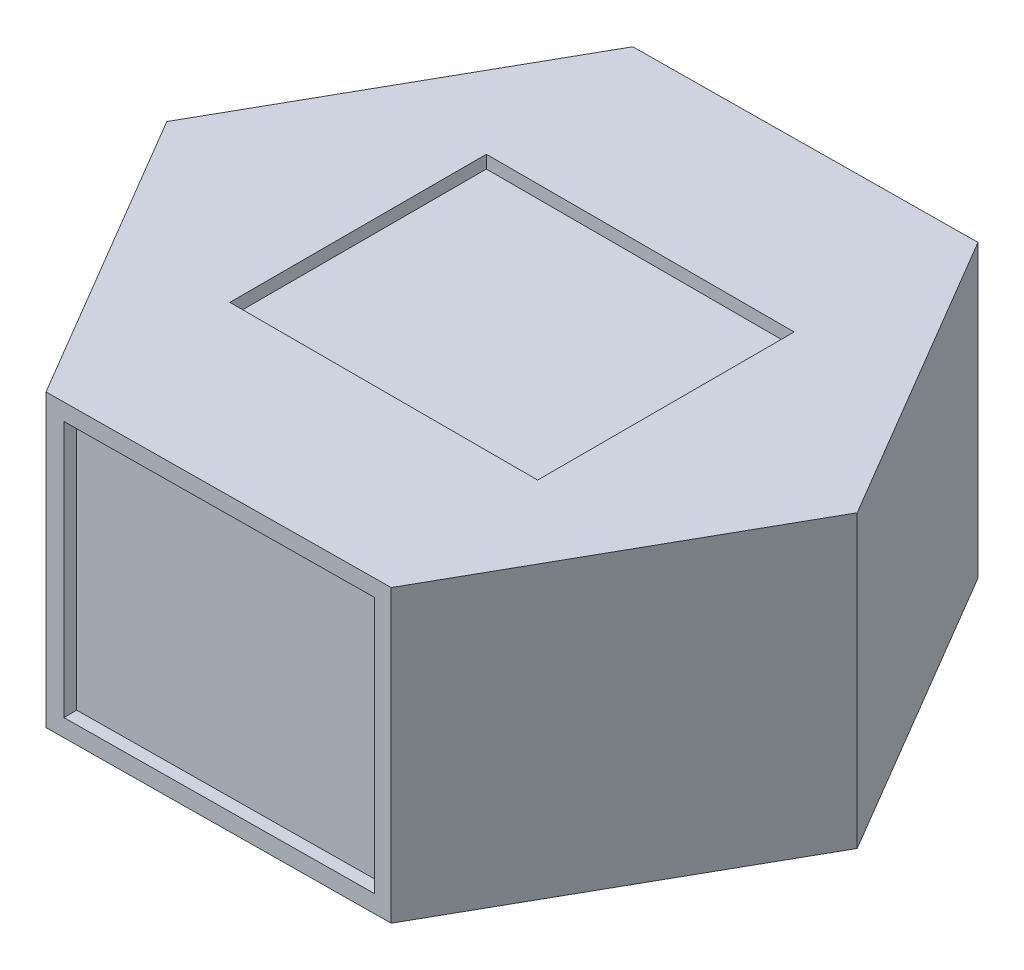
SolidWorks part; units mm, degrees
ref_plane "Front Plane" through (0, 0, 0) normal (0, 0, 1) x (1, 0, 0)
ref_plane "Top Plane" through (0, 0, 0) normal (0, 1, 0) x (1, 0, 0)
ref_plane "Right Plane" through (0, 0, 0) normal (1, 0, 0) x (0, 0, -1)
sketch "Sketch1" plane through (0, 0, 0) normal (0, 1, 0) x (1, 0, 0)
  line L1 (20.3231, -34.4525) -> (39.9983, 0.3741)
  line L2 (39.9983, 0.3741) -> (19.6752, 34.8265)
  line L3 (19.6752, 34.8265) -> (-20.3231, 34.4525)
  line L4 (-20.3231, 34.4525) -> (-39.9983, -0.3741)
  line L5 (-39.9983, -0.3741) -> (-19.6752, -34.8265)
  line L6 (-19.6752, -34.8265) -> (20.3231, -34.4525)
  circle A0 centre (0, 0) radius 34.641 construction
  dimension "D1" = 40
extrude "Boss-Extrude1" add sketch "Sketch1" along normal blind 34
sketch "Sketch2" plane through (0.324, 0, 34.6395) normal (0.0094, 0, 1) x (1, 0, -0.0094)
  line L1 (-17.9218, 32.043) -> (18.0782, 32.043)
  line L2 (-17.9218, 32.043) -> (-17.9218, 2.043)
  line L3 (-17.9218, 2.043) -> (18.0782, 2.043)
  line L4 (18.0782, 32.043) -> (18.0782, 2.043)
  dimension "D1" = 30
  dimension "D2" = 36
extrude "Cut-Extrude1" cut sketch "Sketch2" against normal blind 1.5
sketch "Sketch3" plane through (-0.324, 0, -34.6395) normal (-0.0094, 0, -1) x (-1, 0, 0.0094)
  line L1 (-18.0909, 32.0618) -> (17.9091, 32.0618)
  line L2 (-18.0909, 32.0618) -> (-18.0909, 2.0618)
  line L3 (-18.0909, 2.0618) -> (17.9091, 2.0618)
  line L4 (17.9091, 32.0618) -> (17.9091, 2.0618)
  dimension "D1" = 36
  dimension "D2" = 30
extrude "Cut-Extrude2" cut sketch "Sketch3" against normal blind 1.5
sketch "Sketch4" plane through (0, 34, 0) normal (0, 1, 0) x (1, 0, 0)
  line L1 (-18, 15) -> (18, 15)
  line L2 (-18, 15) -> (-18, -15)
  line L3 (-18, -15) -> (18, -15)
  line L4 (18, 15) -> (18, -15)
  line L5 (-18, 15) -> (18, -15) construction
  line L6 (-18, -15) -> (18, 15) construction
  point P0 (0, 0)
  dimension "D1" = 36
  dimension "D2" = 30
extrude "Cut-Extrude3" cut sketch "Sketch4" against normal blind 1.5
sketch "Sketch5" plane through (0, 0, 0) normal (0, -1, 0) x (1, 0, 0)
  line L1 (37.25, -0.0128) -> (18.6361, 32.253)
  line L2 (18.6361, 32.253) -> (-18.6139, 32.2658)
  line L3 (-18.6139, 32.2658) -> (-37.25, 0.0128)
  line L4 (-37.25, 0.0128) -> (-18.6361, -32.253)
  line L5 (-18.6361, -32.253) -> (18.6139, -32.2658)
  line L6 (18.6139, -32.2658) -> (37.25, -0.0128)
  circle A0 centre (0, 0) radius 32.2594 construction
  dimension "D1" = 2.2
  dimension "D2" = 37.25
extrude "Cut-Extrude5" cut sketch "Sketch5" against normal blind 31.5
sketch "Sketch6" plane through (27.943, 0, 16.1201) normal (-0.8662, 0, -0.4997) x (-0.4997, 0, 0.8662)
  line L0 (-18.625, 0) -> (18.625, 0) construction
  line L1 (-18.6348, 2.5) -> (18.6152, 2.5)
  line L2 (-18.6348, 2.5) -> (-18.6348, 4.422)
  line L3 (-18.6348, 4.422) -> (18.6152, 4.422)
  line L4 (18.6152, 2.5) -> (18.6152, 4.422)
  dimension "D1" = 2.5
  dimension "D2" = 37.25
extrude "Boss-Extrude2" add sketch "Sketch6" along normal blind 5
sketch "Sketch7" plane through (-27.943, 0, -16.1201) normal (0.8662, 0, 0.4997) x (0.4997, 0, -0.8662)
  line L1 (-18.6282, 4.8344) -> (18.6218, 4.8344)
  line L2 (-18.6282, 4.8344) -> (-18.6282, 2.3344)
  line L3 (-18.6282, 2.3344) -> (18.6218, 2.3344)
  line L4 (18.6218, 4.8344) -> (18.6218, 2.3344)
  dimension "D1" = 37.25
  dimension "D2" = 2.5
extrude "Boss-Extrude3" add sketch "Sketch7" along normal blind 5
